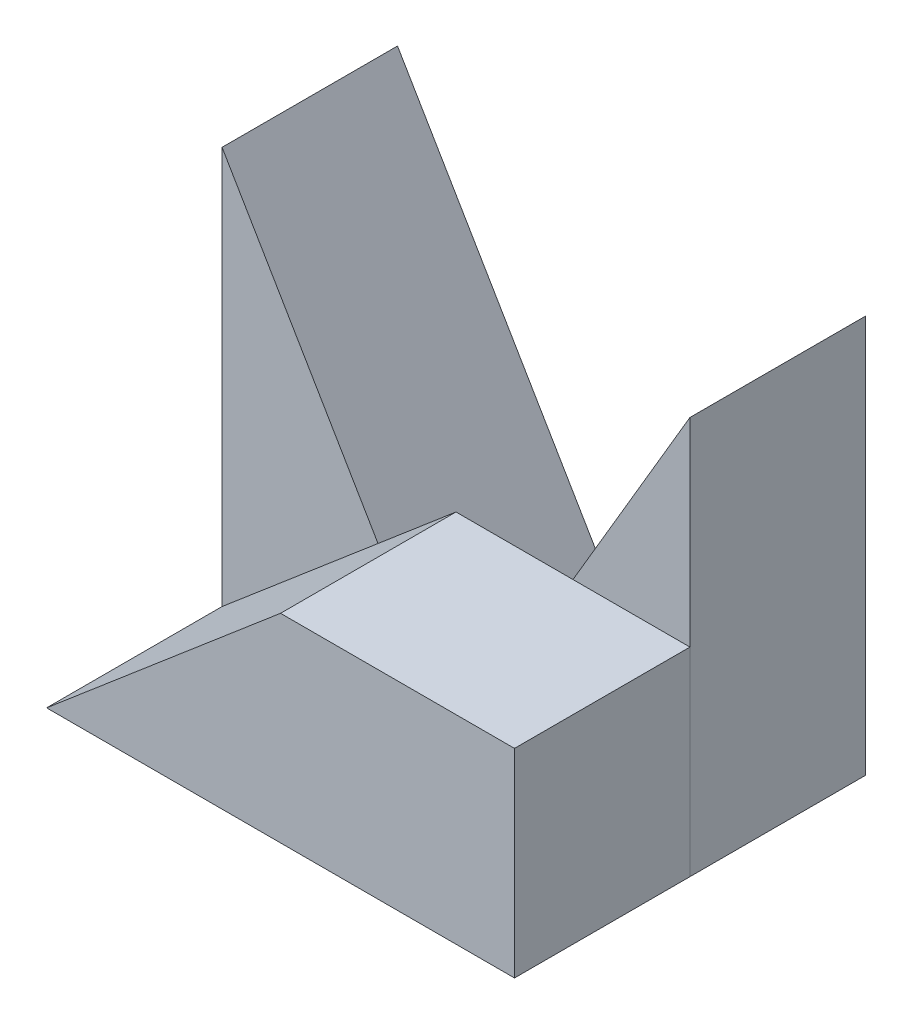
SolidWorks part; units mm, degrees
ref_plane "Front Plane" through (0, 0, 0) normal (0, 0, 1) x (1, 0, 0)
ref_plane "Top Plane" through (0, 0, 0) normal (0, 1, 0) x (1, 0, 0)
ref_plane "Right Plane" through (0, 0, 0) normal (1, 0, 0) x (0, 0, -1)
sketch "Sketch1" plane through (0, 0, 0) normal (0, 0, 1) x (1, 0, 0)
  line L0 (-20285.7143, 0) -> (19714.2857, 0)
  line L1 (19714.2857, 0) -> (19714.2857, 17000)
  line L2 (19714.2857, 17000) -> (-285.7143, 17000)
  line L3 (-285.7143, 17000) -> (-20285.7143, 0)
  dimension "D1" = 40000
  dimension "D2" = 17000
  dimension "D3" = 20000
extrude "Boss-Extrude1" add sketch "Sketch1" against normal blind 15000
sketch "Sketch2" plane through (0, 0, -15000) normal (0, 0, -1) x (-1, 0, 0)
  line L0 (285.7143, 0) -> (20285.7143, 0)
  line L1 (20285.7143, 0) -> (-19714.2857, 0) construction
  line L2 (20285.7143, 0) -> (20285.7143, 34000)
  line L3 (20285.7143, 34000) -> (285.7143, 0)
  dimension "D1" = 20000
  dimension "D2" = 34000
extrude "Boss-Extrude2" add sketch "Sketch2" along normal blind 15000
sketch "Sketch5" plane through (0, 0, -15000) normal (0, 0, -1) x (-1, 0, 0)
  line L0 (285.7143, 0) -> (-19714.2857, 0)
  line L1 (-19714.2857, 0) -> (-19714.2857, 34000)
  line L2 (-19714.2857, 34000) -> (285.7143, 0)
  line L3 (285.7143, 0) -> (283.6269, -4.4716)
  line M5 (285.7143, 17000) -> (-19714.2857, 17000)
  line M6 (-19714.2857, 17000) -> (-19714.2857, 0)
  line M7 (-19714.2857, 0) -> (285.7143, 0)
  dimension "D1" = 34000
extrude "Boss-Extrude16" add sketch "Sketch5" along normal blind 15000 separate body contours L2 L1 M5 | L2 M5 M6 M7
